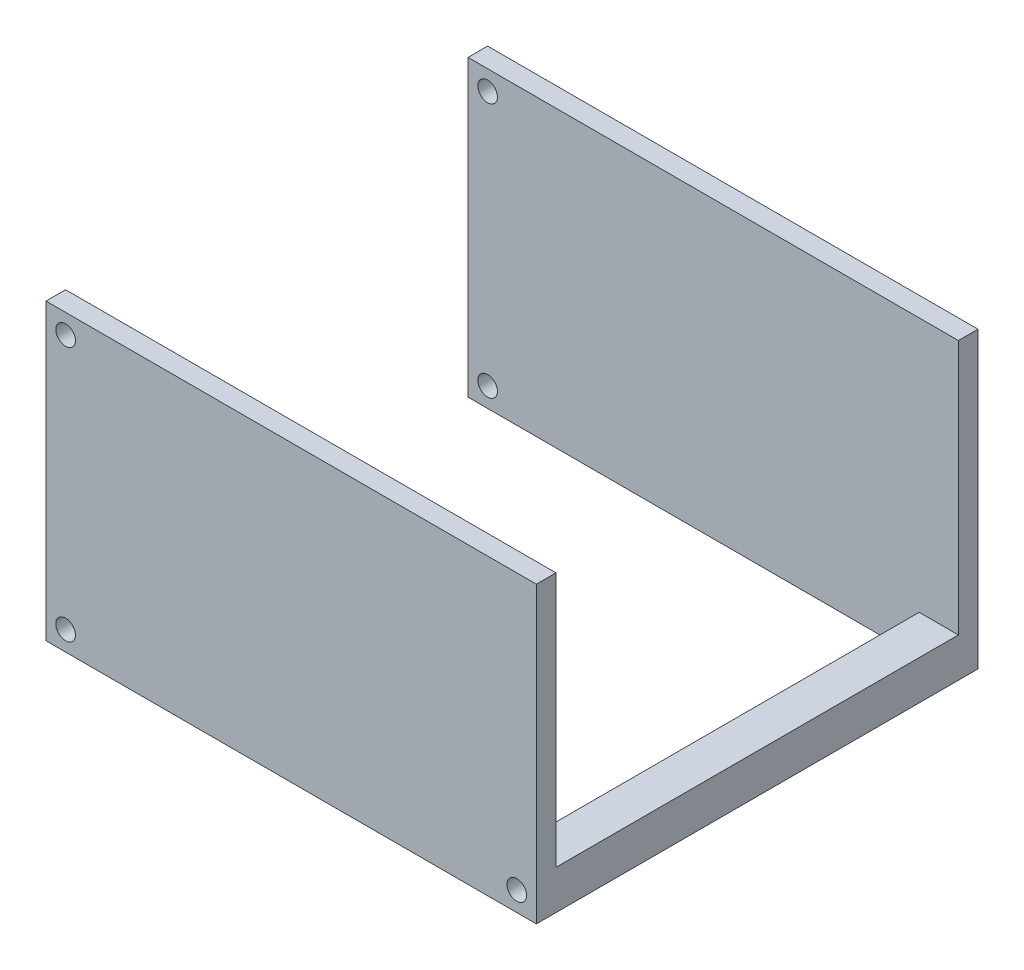
SolidWorks part; units mm, degrees
ref_plane "前视基准面" through (0, 0, 0) normal (0, 0, 1) x (1, 0, 0)
ref_plane "上视基准面" through (0, 0, 0) normal (0, 1, 0) x (1, 0, 0)
ref_plane "右视基准面" through (0, 0, 0) normal (1, 0, 0) x (0, 0, -1)
sketch "草图1" plane through (0, 0, 0) normal (0, 0, 1) x (1, 0, 0)
  line L0 (0, 0) -> (50000, 0) construction
  line L1 (0, 0) -> (0, 50000) construction
  line L3 (-25, 15) -> (25, 15)
  line L4 (-25, 15) -> (-25, -15)
  line L5 (-25, -15) -> (25, -15)
  line L6 (25, 15) -> (25, -15)
  circle A0 centre (-23, -13) radius 1
  circle A1 centre (-23, 13) radius 1
  dimension "D1" = 2
  dimension "D2" = 50
  dimension "D3" = 30
  dimension "D4" = 2
extrude "凸台-拉伸1" add sketch "草图1" along normal blind 45.03
sketch "草图2" plane through (0, 15, 0) normal (0, 1, 0) x (1, 0, 0)
  line L0 (-25, -22.515) -> (49975, -22.515) construction
  line L1 (-25, -45.03) -> (-25, 0) construction
  line L2 (0, -45.03) -> (0, 49954.97) construction
  line L3 (25, -45.03) -> (-25, -45.03) construction
  line L4 (25, 0) -> (-25, 0) construction
  line L5 (-25, -2) -> (21, -2)
  line L6 (-25, -2) -> (-25, -43.03)
  line L7 (-25, -43.03) -> (21, -43.03)
  line L8 (21, -2) -> (21, -43.03)
  line L9 (25, -45.03) -> (25, 0) construction
  point P4 (-25, -22.515)
  point P9 (0, -45.03)
  dimension "D1" = 2
  dimension "D2" = 4
extrude "切除-拉伸1" cut sketch "草图2" against normal blind 45.03
sketch "草图3" plane through (0, 0, 45.03) normal (0, 0, 1) x (1, 0, 0)
  line L0 (25, -15) -> (25, 15) construction
  line L1 (-25, -15) -> (25, -15) construction
  circle A0 centre (23, -13) radius 1
  dimension "D1" = 2
  dimension "D2" = 2
extrude "切除-拉伸2" cut sketch "草图3" against normal blind 45.03 contours A0
sketch "草图4" plane through (0, 15, 0) normal (0, 1, 0) x (1, 0, 0)
  line L0 (25, -45.03) -> (25, 0) construction
  line L1 (21, -2) -> (25, -2)
  line L2 (21, -2) -> (21, -43.03)
  line L3 (21, -43.03) -> (25, -43.03)
  line L4 (25, -2) -> (25, -43.03)
extrude "切除-拉伸3" cut sketch "草图4" against normal blind 26
